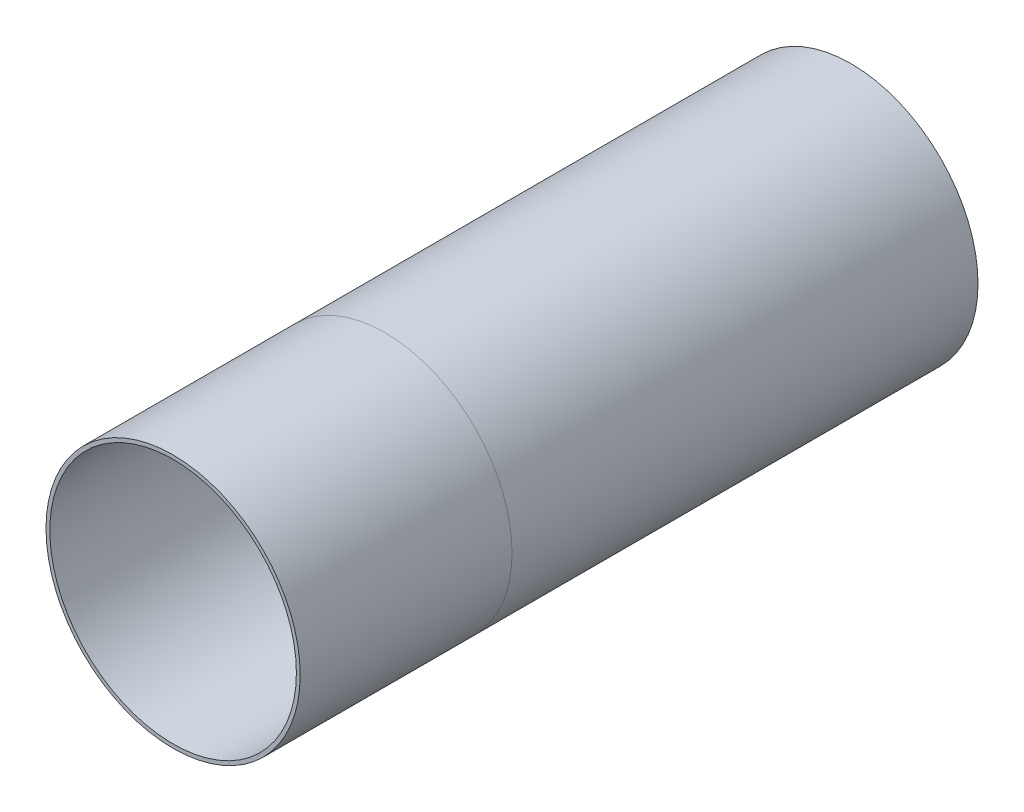
SolidWorks part; units mm, degrees
ref_plane "Plan de face" through (0, 0, 0) normal (0, 0, 1) x (1, 0, 0)
ref_plane "Plan de dessus" through (0, 0, 0) normal (0, 1, 0) x (1, 0, 0)
ref_plane "Plan de droite" through (0, 0, 0) normal (1, 0, 0) x (0, 0, -1)
sketch "Esquisse2" plane through (0, 0, 0) normal (0, 0, 1) x (1, 0, 0)
  circle A0 centre (0, 0) radius 76.1746
  circle A1 centre (0, 0) radius 73.914
  dimension "D1" = 152.3492
  dimension "D2" = 147.828
extrude "Boss.-Extru.1" add sketch "Esquisse2" along normal blind 279.4
sketch "Esquisse3" plane through (0, 0, 279.4) normal (0, 0, 1) x (1, 0, 0)
  circle A0 centre (0, 0) radius 76.2
  circle A1 centre (0, 0) radius 73.914
  dimension "D1" = 147.828
extrude "Boss.-Extru.2" add sketch "Esquisse3" along normal blind 127
